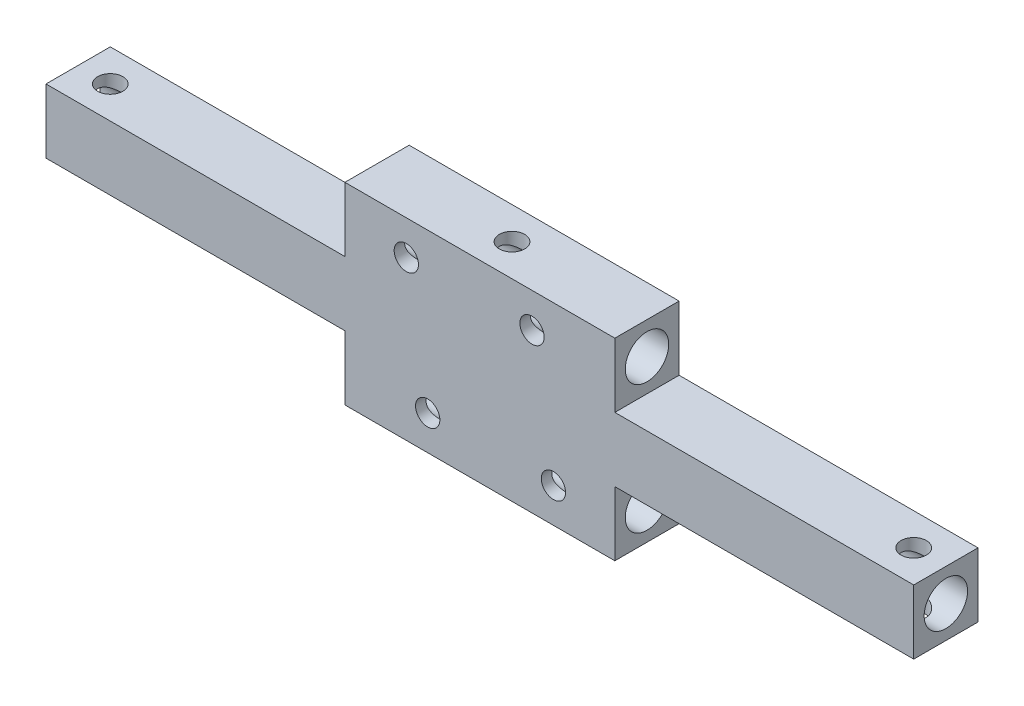
SolidWorks part; units mm, degrees
material "Hexcel AS4C (3000 Filaments)"
ref_plane "Front Plane" through (0, 0, 0) normal (0, 0, 1) x (1, 0, 0)
ref_plane "Top Plane" through (0, 0, 0) normal (0, 1, 0) x (1, 0, 0)
ref_plane "Right Plane" through (0, 0, 0) normal (1, 0, 0) x (0, 0, -1)
sketch "Sketch1" plane through (0, 0, 0) normal (0, 0, 1) x (1, 0, 0)
  line L0 (-42.8625, 0) -> (42.8625, 0)
  line L1 (-42.8625, 6.35) -> (42.8625, 6.35)
  line L2 (-42.8625, 6.35) -> (-42.8625, 0)
  line L3 (0, 0) -> (0, 19.2823) construction
  line L4 (42.8625, 6.35) -> (42.8625, 0)
  line L5 (-13.335, 0) -> (13.335, 0)
  line L6 (-13.335, 0) -> (-13.335, -6.35)
  line L7 (-13.335, -6.35) -> (13.335, -6.35)
  line L8 (13.335, 0) -> (13.335, -6.35)
  line L9 (-13.335, 6.35) -> (13.335, 6.35)
  line L10 (-13.335, 6.35) -> (-13.335, 12.7)
  line L11 (-13.335, 12.7) -> (13.335, 12.7)
  line L12 (13.335, 6.35) -> (13.335, 12.7)
  line L13 (-38.735, 3.175) -> (38.735, 3.175) construction
  point P4 (0, 6.35)
  point P5 (0, 12.7)
  point P6 (0, 0)
  point P12 (21.2579, -8.9066)
  point P13 (0, -6.35)
  point P25 (0, 3.175)
  dimension "D1" = 6.35
  dimension "D2" = 85.725
  dimension "D3" = 6.35
  dimension "D4" = 26.67
  dimension "D5" = 6.35
  dimension "D6" = 26.67
extrude "Boss-Extrude1" add sketch "Sketch1" along normal blind 6.35
sketch "Sketch2" plane through (42.8625, 0, 0) normal (1, 0, 0) x (0, 0, -1)
  circle A0 centre (-3.175, 3.175) radius 2.1463
  dimension "D1" = 4.2926
extrude "Cut-Extrude1" cut sketch "Sketch2" against normal up to surface (85.725 mm away) up to face at (-42.8625, 3.175, 3.175)
sketch "Sketch4" plane through (13.335, 0, 0) normal (1, 0, 0) x (0, 0, -1)
  circle A0 centre (-3.175, 9.525) radius 2.1463
extrude "Cut-Extrude2" cut sketch "Sketch4" against normal up to surface (26.67 mm away) up to face at (-13.335, 9.525, 3.175)
sketch "Sketch5" plane through (13.335, 0, 0) normal (1, 0, 0) x (0, 0, -1)
  circle A0 centre (-3.175, -3.175) radius 2.1463
extrude "Cut-Extrude3" cut sketch "Sketch5" against normal up to surface (26.67 mm away) up to face at (-13.335, -3.175, 3.175)
sketch "Sketch6" plane through (0, 12.7, 0) normal (0, 1, 0) x (1, 0, 0)
  circle A0 centre (0, -3.175) radius 1.2515
extrude "Cut-Extrude4" cut sketch "Sketch6" against normal up to surface (19.05 mm away) up to face at (0, -6.35, 3.175)
sketch "Sketch8" plane through (0, 0, 6.35) normal (0, 0, 1) x (1, 0, 0)
  line L0 (-5.1531, -2.9443) -> (5.1531, 9.2943) construction
  line L1 (-7.2667, 9.2943) -> (7.2667, -2.9443) construction
  circle A4 centre (7.2667, -2.9443) radius 1.2
  circle A6 centre (-5.1531, -2.9443) radius 1.2
  circle A16 centre (5.1531, 9.2943) radius 1.2
  circle A18 centre (-7.2667, 9.2943) radius 1.2
  point P0 (0, 3.175)
  point P1 (0, 3.175)
  point P2 (0, 3.175)
  dimension "D1" = 12.4197
  dimension "D2" = 12.4197
  dimension "D3" = 19
  dimension "D4" = 16
  dimension "D5" = 12.4197
extrude "Cut-Extrude6" cut sketch "Sketch8" against normal up to surface (6.35 mm away) up to face at (0, 3.175, 0)
sketch "Sketch9" plane through (0, 6.35, 0) normal (0, 1, 0) x (1, 0, 0)
  line L0 (42.8625, -6.35) -> (42.8625, 0) construction
  line L1 (-42.8625, -1.0287) -> (-42.8625, -5.3213) construction
  circle A0 centre (39.6875, -3.175) radius 1.25
  circle A1 centre (-39.6875, -3.175) radius 1.25
  dimension "D1" = 2.5
  dimension "D3" = 3.175
  dimension "D2" = 3.175
extrude "Cut-Extrude7" cut sketch "Sketch9" against normal up to surface (6.35 mm away) up to face at (28.0987, 0, 3.175)
